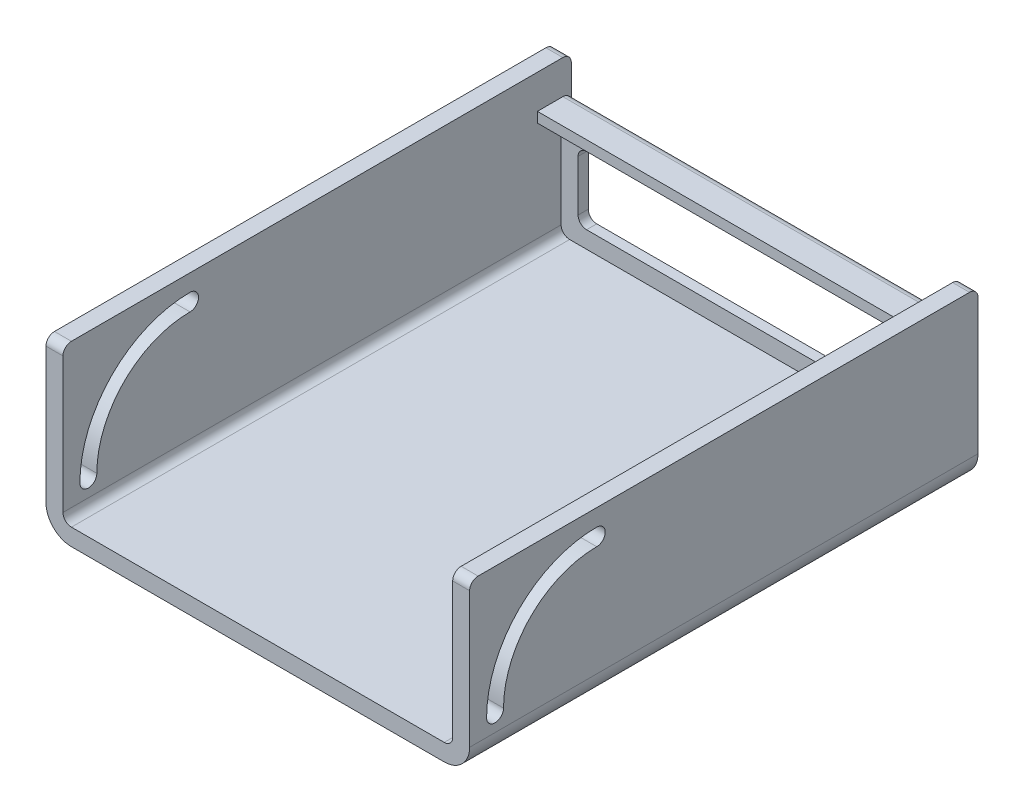
SolidWorks part; units mm, degrees
ref_plane "Front Plane" through (0, 0, 0) normal (0, 0, 1) x (1, 0, 0)
ref_plane "Top Plane" through (0, 0, 0) normal (0, 1, 0) x (1, 0, 0)
ref_plane "Right Plane" through (0, 0, 0) normal (1, 0, 0) x (0, 0, -1)
sketch "Sketch1" plane through (0, 0, 0) normal (0, 0, 1) x (1, 0, 0)
  line L0 (0, 0) -> (0, 89.0133) construction
  line L1 (125, 0) -> (-125, 0)
  line L2 (-125, 0) -> (-125, 100)
  line L3 (125, 0) -> (125, 100)
  dimension "D1" = 250
  dimension "D2" = 100
extrude "Extrude-Thin1" add sketch "Sketch1" against normal blind 300 thin
sketch "Sketch2" plane through (0, 0, 0) normal (-1, 0, 0) x (0, 0, 1)
  line L0 (0, 100) -> (0, 15) construction
  line L1 (-300, 100) -> (0, 100) construction
  arc A0 (-75, 85) -> (-15, 25) centre (-75, 25) cw construction
  arc A1 (-75, 80) -> (-20, 25) centre (-75, 25) cw
  arc A2 (-75, 90) -> (-10, 25) centre (-75, 25) cw
  arc A3 (-75, 80) -> (-75, 90) centre (-75, 85) cw
  arc A4 (-20, 25) -> (-10, 25) centre (-15, 25) ccw
  dimension "D3" = 60
  dimension "D1" = 75
  dimension "D2" = 75
  dimension "D4" = 5
  dimension "D5" = 5
extrude "Cut-Extrude1" cut sketch "Sketch2" against normal through all and the other way through all
sketch "Sketch3" plane through (115, 0, 0) normal (-1, 0, 0) x (0, 0, 1)
  line L0 (-300, 100) -> (-300, 15) construction
  line L1 (-300, 80) -> (-280, 80)
  line L3 (-294, 74) -> (-280, 74)
  line L4 (-280, 80) -> (-280, 74)
  line L5 (-294, 74) -> (-294, 10)
  line L6 (-300, 100) -> (0, 100) construction
  line L7 (-300, 80) -> (-300, 10)
  line L9 (-300, 10) -> (-294, 10)
  line L10 (-300, 10) -> (0, 10) construction
  dimension "D1" = 6
  dimension "D2" = 20
  dimension "D3" = 20
  dimension "D4" = 6
extrude "Boss-Extrude1" add sketch "Sketch3" along normal up to surface (230 mm away) up to face at (-115, 59.9632, -40.0368)
sketch "Sketch4" plane through (0, 0, -300) normal (0, 0, -1) x (-1, 0, 0)
  line L1 (-100, 60) -> (100, 60)
  line L2 (-105, 55) -> (-105, 25)
  line L3 (-100, 20) -> (100, 20)
  line L4 (105, 55) -> (105, 25)
  line L5 (115, 90) -> (115, 80) construction
  line L6 (115, 80) -> (-115, 80) construction
  line L7 (0, 0) -> (0, 80) construction
  line L8 (-110, 0) -> (110, 0) construction
  arc A0 (100, 20) -> (105, 25) centre (100, 25) ccw
  arc A1 (100, 60) -> (105, 55) centre (100, 55) cw
  arc A2 (-100, 60) -> (-105, 55) centre (-100, 55) ccw
  arc A3 (-105, 25) -> (-100, 20) centre (-100, 25) ccw
  point P15 (105, 20)
  point P18 (105, 60)
  point P21 (-105, 60)
  dimension "D4" = 5
  dimension "D1" = 210
  dimension "D2" = 40
  dimension "D3" = 20
extrude "Cut-Extrude2" cut sketch "Sketch4" against normal up to next
fillet "Fillet1" radius 5 5 edges at (120, 100, 0) (120, 100, -300) (-120, 100, -300) (-120, 100, 0) (0, 80, -300)
